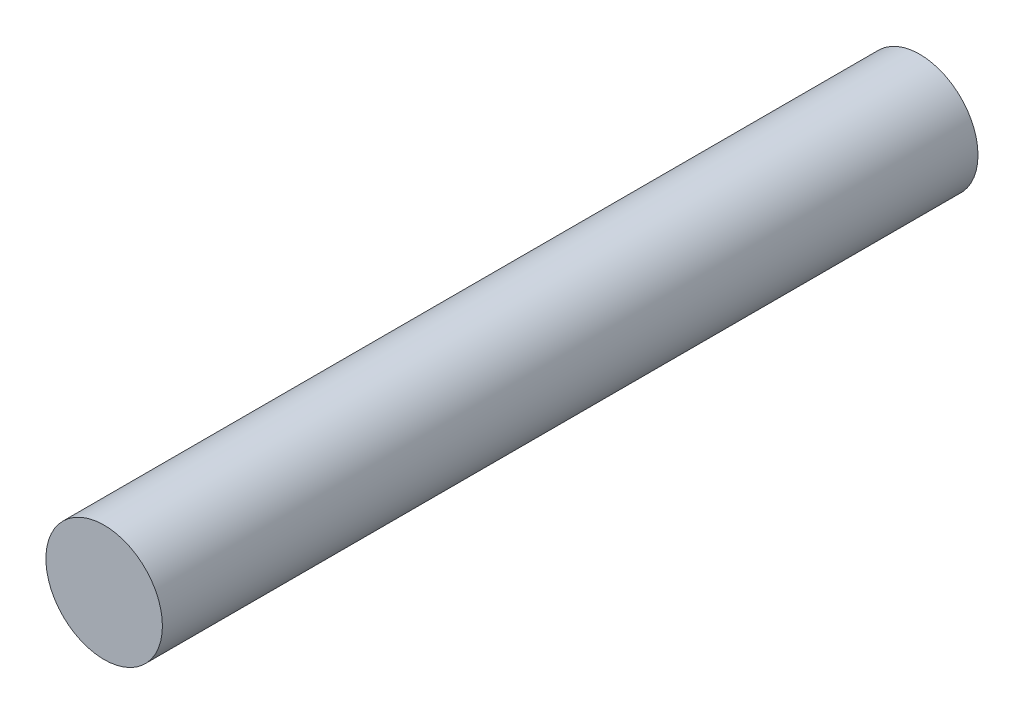
SolidWorks part; units mm, degrees
ref_plane "Front Plane" through (0, 0, 0) normal (0, 0, 1) x (1, 0, 0)
ref_plane "Top Plane" through (0, 0, 0) normal (0, 1, 0) x (1, 0, 0)
ref_plane "Right Plane" through (0, 0, 0) normal (1, 0, 0) x (0, 0, -1)
sketch "Sketch1" plane through (0, 0, 0) normal (0, 0, 1) x (1, 0, 0)
  circle A0 centre (0, 0) radius 25
  dimension "D1" = 50
extrude "Boss-Extrude1" add sketch "Sketch1" along normal blind 350
